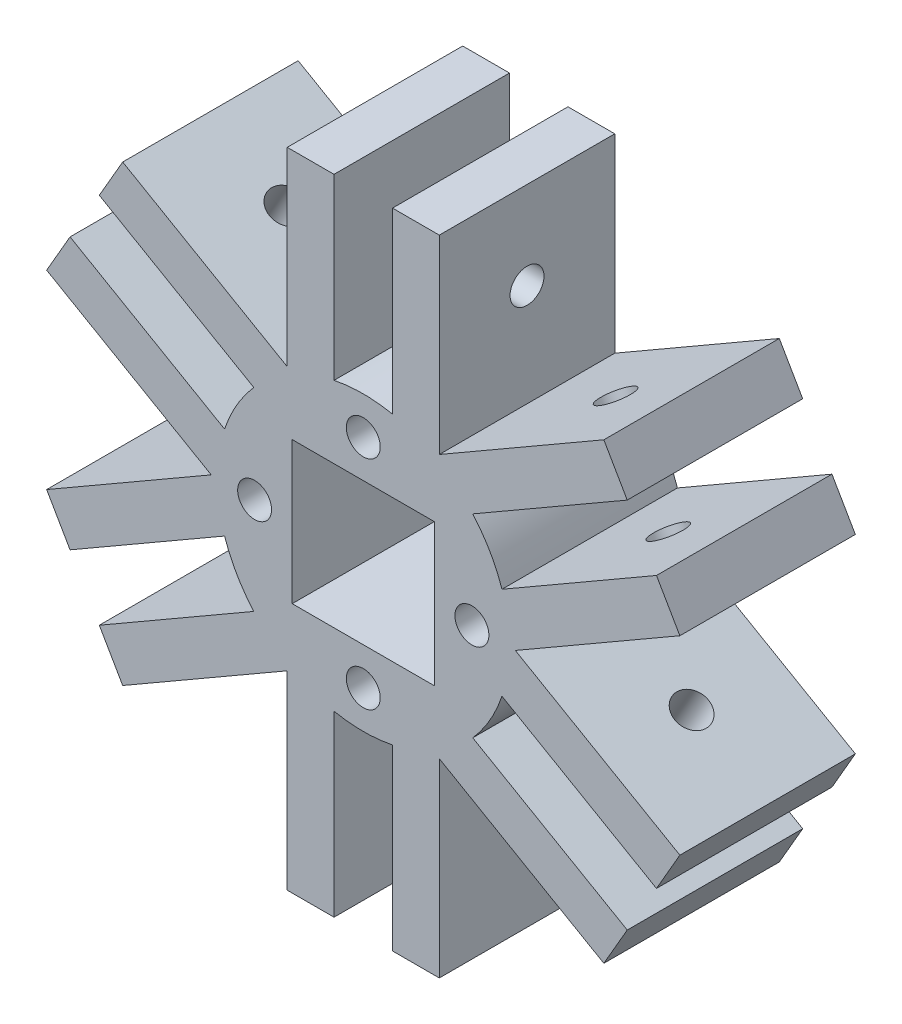
SolidWorks part; units mm, degrees
ref_plane "Front Plane" through (0, 0, 0) normal (0, 0, 1) x (1, 0, 0)
ref_plane "Top Plane" through (0, 0, 0) normal (0, 1, 0) x (1, 0, 0)
ref_plane "Right Plane" through (0, 0, 0) normal (1, 0, 0) x (0, 0, -1)
sketch "Sketch1" plane through (0, 0, 0) normal (0, 0, 1) x (1, 0, 0)
  circle A0 centre (0, 0) radius 12.5
  dimension "D2" = 25
extrude "Boss-Extrude1" add sketch "Sketch1" along normal mid plane 15
sketch "Sketch4" plane through (0, 0, 7.5) normal (0, 0, 1) x (1, 0, 0)
  line L0 (13.75, 0) -> (-13.75, 0) construction
  line L2 (-6.5, 0) -> (-2.5, 0)
  line L3 (0, 0) -> (0, 15.8331) construction
  line L4 (-6.5, 0) -> (-6.5, 27.5)
  line L5 (-6.5, 27.5) -> (-2.5, 27.5)
  line L6 (-2.5, 0) -> (-2.5, 27.5)
  line L7 (0, -13.75) -> (0, 13.75) construction
  line L8 (6.5, 27.5) -> (2.5, 27.5)
  line L9 (2.5, 0) -> (2.5, 27.5)
  line L10 (6.5, 0) -> (2.5, 0)
  line L11 (6.5, 0) -> (6.5, 27.5)
  dimension "D1" = 27.5
  dimension "D3" = 2.5
  dimension "D2" = 4
extrude "Boss-Extrude3" add sketch "Sketch4" against normal up to surface (15 mm away) up to face at (12.5, 0, -7.5)
pattern_circular "CirPattern7" count 6 over 360 about axis through (0, 0, 0) along (0, 0, 1) of "Boss-Extrude3"
sketch "Sketch7" plane through (-6.5, 0, 0) normal (-1, 0, 0) x (0, 0, 1)
  line L0 (-7.5, 27.5) -> (7.5, 27.5) construction
  line L1 (-7.5, 11.2583) -> (-7.5, 27.5) construction
  circle A0 centre (0, 20) radius 1.45
  circle A1 centre (40, 20) radius 1.45
  circle A2 centre (80, 20) radius 1.45
  circle A3 centre (120, 20) radius 1.45
  circle A4 centre (160, 20) radius 1.45
  dimension "D1" = 2.9
  dimension "D2" = 7.5
  dimension "D3" = 7.5
  dimension "D4" = 5
extrude "Cut-Extrude2" cut sketch "Sketch7" against normal blind 17
pattern_circular "CirPattern9" count 6 over 360 of "Cut-Extrude2"
sketch "Sketch8" plane through (0, 0, 7.5) normal (0, 0, 1) x (1, 0, 0)
  line L2 (-6.075, 6.075) -> (6.075, 6.075)
  line L3 (-6.075, 6.075) -> (-6.075, -6.075)
  line L4 (-6.075, -6.075) -> (6.075, -6.075)
  line L5 (6.075, 6.075) -> (6.075, -6.075)
  line L6 (-6.075, 6.075) -> (6.075, -6.075) construction
  line L7 (-6.075, -6.075) -> (6.075, 6.075) construction
  point P5 (0, 0)
  point P14 (0, 0)
  dimension "D1" = 12.15
extrude "Cut-Extrude3" cut sketch "Sketch8" against normal up to next
sketch "Sketch9" plane through (0, 0, 7.5) normal (0, 0, 1) x (1, 0, 0)
  line L0 (13.75, 0) -> (-13.75, 0) construction
  line L1 (6.075, -6.075) -> (6.075, 6.075) construction
  circle A0 centre (9.2875, 0) radius 1.45
  circle A1 centre (0, -9.2875) radius 1.45
  circle A2 centre (-9.2875, 0) radius 1.45
  circle A3 centre (0, 9.2875) radius 1.45
  point P14 (0, 0)
  dimension "D1" = 2.9
  dimension "D2" = 3.2125
  dimension "D3" = 4
extrude "Cut-Extrude4" cut sketch "Sketch9" against normal blind 10
equation "\"drumDiameter\" = 25"
equation "\"D2@Sketch1\"=\"drumDiameter\""
equation "\"drumLength\" = 15"
equation "\"D1@Sketch4\"=\"drumDiameter\"*(0.5+\"drumAbove\")"
equation "\"foamThickness\" = 5"
equation "\"D3@Sketch4\"=\"foamThickness\"/2"
equation "\"drumAbove\"= 0.6"
equation "\"D2@Sketch7\"=\"drumDiameter\"*\"drumAbove\"/2"
equation "\"holderThicc\" = 4"
equation "\"D2@Sketch4\"=\"holderThicc\""
equation "\"D1@Boss-Extrude1\"=\"drumLength\""
equation "\"squareBarLength\"=12.15"
equation "\"D1@Sketch8\"=\"squareBarLength\""
equation "\"D2@Sketch9\"=(\"drumDiameter\"/2-\"squareBarLength\"/2)/2"
